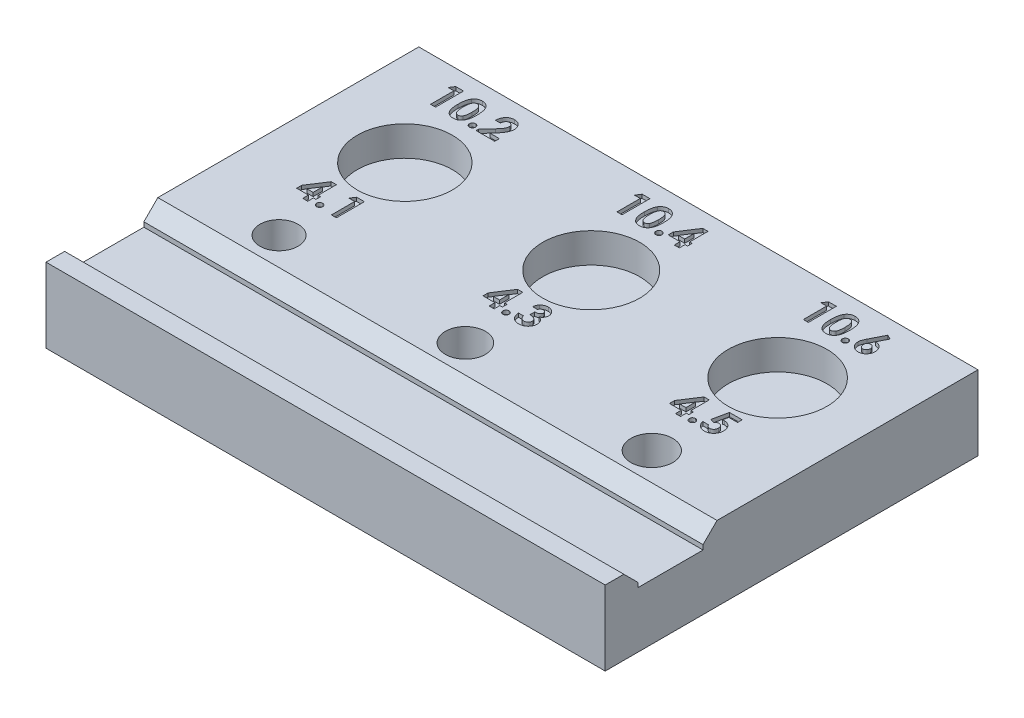
SolidWorks part; units mm, degrees
ref_plane "Alzado" through (0, 0, 0) normal (0, 0, 1) x (1, 0, 0)
ref_plane "Planta" through (0, 0, 0) normal (0, 1, 0) x (1, 0, 0)
ref_plane "Vista lateral" through (0, 0, 0) normal (1, 0, 0) x (0, 0, -1)
sketch "Croquis1" plane through (0, 0, 0) normal (0, 1, 0) x (1, 0, 0)
  line L0 (-30, -20) -> (30, -20)
  line L1 (30, -20) -> (30, 20)
  line L2 (30, 20) -> (-30, 20)
  line L3 (-30, 20) -> (-30, -20)
extrude "Saliente-Extruir1" add sketch "Croquis1" against normal blind 8
sketch "Croquis2" plane through (0, 0, 0) normal (0, 1, 0) x (1, 0, 0)
  circle A0 centre (-20, 8.5) radius 5.1
sketch "Croquis3" plane through (0, 0, 0) normal (0, 1, 0) x (1, 0, 0)
  circle A0 centre (0, 8.5) radius 5.2
sketch "Croquis4" plane through (0, 0, 0) normal (0, 1, 0) x (1, 0, 0)
  circle A0 centre (20, 8.5) radius 5.3
sketch "Croquis5" plane through (0, 0, 0) normal (0, 1, 0) x (1, 0, 0)
  circle A0 centre (-20, -5) radius 2.05
sketch "Croquis6" plane through (0, 0, 0) normal (0, 1, 0) x (1, 0, 0)
  circle A0 centre (0, -5) radius 2.15
sketch "Croquis7" plane through (0, 0, 0) normal (0, 1, 0) x (1, 0, 0)
  circle A0 centre (20, -5) radius 2.25
sketch "Croquis8" plane through (0, 0, 0) normal (0, 1, 0) x (1, 0, 0)
  line L0 (-30, -16.5) -> (30, -16.5)
  line L1 (30, -16.5) -> (30, -9.5)
  line L2 (30, -9.5) -> (-30, -9.5)
  line L3 (-30, -9.5) -> (-30, -16.5)
extrude "Cortar-Extruir1" cut sketch "Croquis2" against normal blind 3.2
extrude "Cortar-Extruir2" cut sketch "Croquis3" against normal blind 3.2
extrude "Cortar-Extruir3" cut sketch "Croquis4" against normal blind 3.2
extrude "Cortar-Extruir4" cut sketch "Croquis5" against normal blind 4.3
extrude "Cortar-Extruir5" cut sketch "Croquis6" against normal blind 4.3
extrude "Cortar-Extruir6" cut sketch "Croquis7" against normal blind 4.3
extrude "Cortar-Extruir7" cut sketch "Croquis8" against normal blind 2
chamfer "Chaflán1" distance 1.5 angle 45 2 edges at (0, 0, 9.5) (0, 0, 16.5)
sketch "Croquis9" plane through (0, 0, 0) normal (0, 1, 0) x (1, 0, 0)
  text T0 "10.2" font "Century Gothic" height 3
  text T1 "10.4" font "Century Gothic" height 3
  text T2 "10.6" font "Century Gothic" height 3
  text T3 "4.1" font "Century Gothic" height 3
  text T4 "4.3" font "Century Gothic" height 3
  text T5 "4.5" font "Century Gothic" height 3
extrude "Cortar-Extruir8" cut sketch "Croquis9" against normal blind 0.4
